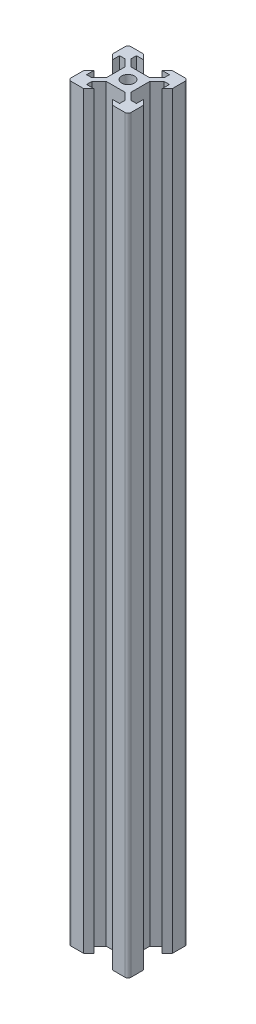
SolidWorks part; units mm, degrees
material "1060 Alloy"
ref_plane "Front Plane" through (0, 0, 0) normal (0, 0, 1) x (1, 0, 0)
ref_plane "Top Plane" through (0, 0, 0) normal (0, 1, 0) x (1, 0, 0)
ref_plane "Right Plane" through (0, 0, 0) normal (1, 0, 0) x (0, 0, -1)
ref_plane "End Plane" through (0, 250, 0) normal (0, 1, 0) x (1, 0, 0)
sketch "MasterLayoutSketch" plane through (0, 0, 0) normal (0, 1, 0) x (1, 0, 0)
  line L0 (-8.325, 3.1) -> (-8.325, 5.5)
  line L1 (-10, -10) -> (10, -10) construction
  line L2 (-10, -10) -> (-10, 10) construction
  line L3 (-10, 10) -> (10, 10) construction
  line L4 (10, -10) -> (10, 10) construction
  line L5 (-10, -10) -> (10, 10) construction
  line L6 (-10, 10) -> (10, -10) construction
  line L7 (-4.775, 10) -> (-3.1, 8.325)
  line L10 (-8.325, 5.5) -> (-6.5607, 5.5)
  line L11 (-10, 4.775) -> (-8.325, 3.1)
  line L12 (-5.5, 8.325) -> (-5.5, 6.5607)
  line L13 (-3.1, 8.325) -> (-5.5, 8.325)
  line L14 (-10, 10) -> (-10, 4.775)
  line L19 (3.1, 8.325) -> (5.5, 8.325)
  line L20 (10, 4.775) -> (8.325, 3.1)
  line L21 (-10, 10) -> (-4.775, 10)
  line L22 (-6.5607, 5.5) -> (-4.1607, 3.1)
  line L23 (-5.5, 6.5607) -> (-3.1, 4.1607)
  line L24 (5.5, 8.325) -> (5.5, 6.5607)
  line L25 (4.775, 10) -> (3.1, 8.325)
  line L26 (8.325, 5.5) -> (6.5607, 5.5)
  line L27 (8.325, 3.1) -> (8.325, 5.5)
  line L28 (10, 10) -> (4.775, 10)
  line L29 (10, 10) -> (10, 4.775)
  line L30 (5.5, 6.5607) -> (3.1, 4.1607)
  line L31 (6.5607, 5.5) -> (4.1607, 3.1)
  line L32 (8.325, -3.1) -> (8.325, -5.5)
  line L33 (4.775, -10) -> (3.1, -8.325)
  line L34 (8.325, -5.5) -> (6.5607, -5.5)
  line L35 (10, -4.775) -> (8.325, -3.1)
  line L36 (5.5, -8.325) -> (5.5, -6.5607)
  line L37 (3.1, -8.325) -> (5.5, -8.325)
  line L38 (10, -10) -> (10, -4.775)
  line L39 (10, -10) -> (4.775, -10)
  line L40 (6.5607, -5.5) -> (4.1607, -3.1)
  line L41 (5.5, -6.5607) -> (3.1, -4.1607)
  line L42 (-3.1, -8.325) -> (-5.5, -8.325)
  line L43 (-10, -4.775) -> (-8.325, -3.1)
  line L44 (-5.5, -8.325) -> (-5.5, -6.5607)
  line L45 (-4.775, -10) -> (-3.1, -8.325)
  line L46 (-8.325, -5.5) -> (-6.5607, -5.5)
  line L47 (-8.325, -3.1) -> (-8.325, -5.5)
  line L48 (-10, -10) -> (-4.775, -10)
  line L49 (-10, -10) -> (-10, -4.775)
  line L50 (-5.5, -6.5607) -> (-3.1, -4.1607)
  line L51 (-6.5607, -5.5) -> (-4.1607, -3.1)
  line L52 (-4.1607, 3.1) -> (-4.1607, -3.1)
  line L53 (-3.1, -4.1607) -> (3.1, -4.1607)
  line L54 (4.1607, -3.1) -> (4.1607, 3.1)
  line L55 (-3.1, 4.1607) -> (3.1, 4.1607)
  circle A0 centre (0, 0) radius 2.1
  point P0 (0, 0)
  point P9 (0, 0)
  dimension "D6" = 4.2
  dimension "D1" = 20
  dimension "D2" = 4
  dimension "D3" = 11
  dimension "D4" = 9.55
  dimension "D5" = 6.2
  dimension "D7" = 1.5
extrude "Main Extrusion" add sketch "MasterLayoutSketch" along normal up to surface (250 mm away) up to plane "End Plane"
fillet "Edge Fillets" radius 1 4 edges at (10, 125, -10) (10, 125, 10) (-10, 125, 10) (-10, 125, -10)
